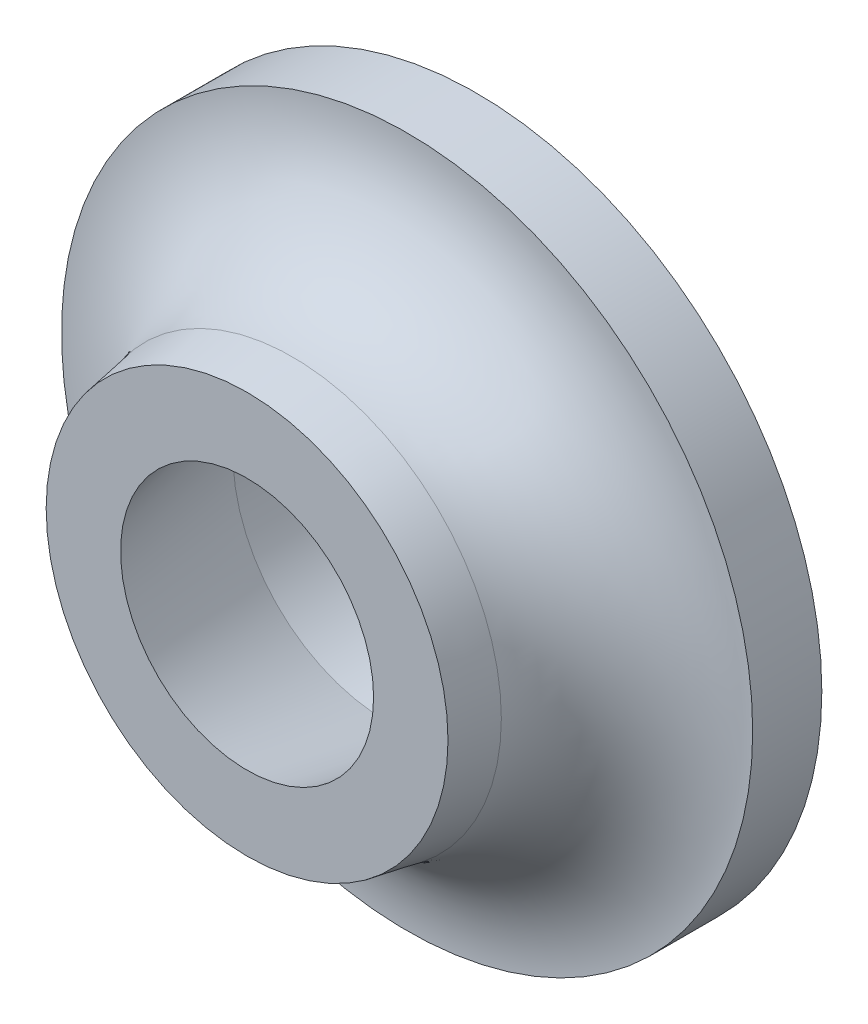
SolidWorks part; units mm, degrees
material "ABS"
ref_plane "Front Plane" through (0, 0, 0) normal (0, 0, 1) x (1, 0, 0)
ref_plane "Top Plane" through (0, 0, 0) normal (0, 1, 0) x (1, 0, 0)
ref_plane "Right Plane" through (0, 0, 0) normal (1, 0, 0) x (0, 0, -1)
sketch "Sketch1" plane through (0, 0, 0) normal (1, 0, 0) x (0, 0, -1)
  line L0 (-51.4955, 0) -> (51.4955, 0) construction
  line L2 (0.508, 14.5345) -> (3.7884, 15.1129)
  line L3 (12.0846, 25) -> (17.0846, 25)
  line L6 (10.5846, 11.1) -> (17.0846, 11.1)
  line L7 (17.0846, 11.1) -> (17.0846, 25)
  line L9 (0.508, 9.1513) -> (0.508, 14.5345)
  line L11 (0.508, 9.1513) -> (10.5846, 11.1)
  arc A0 (3.7884, 15.1129) -> (12.0846, 25) centre (2.045, 25) ccw
  dimension "D3" = 5
  dimension "D4" = 25
  dimension "D1" = 11.1
  dimension "D6" = 6.5
revolve "Revolve1" add sketch "Sketch1" angle 360 about L0
